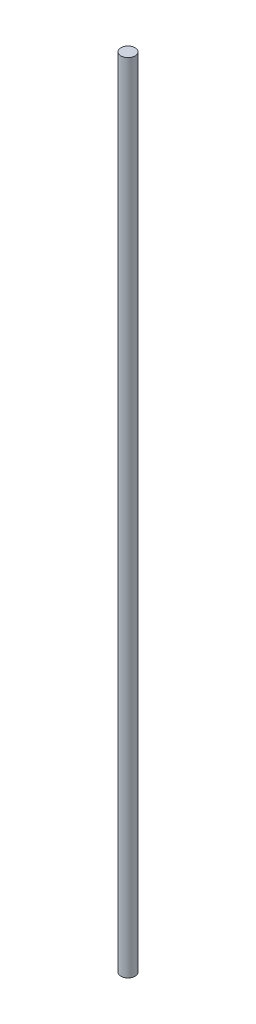
SolidWorks part; units mm, degrees
ref_plane "Front Plane" through (0, 0, 0) normal (0, 0, 1) x (1, 0, 0)
ref_plane "Top Plane" through (0, 0, 0) normal (0, 1, 0) x (1, 0, 0)
ref_plane "Right Plane" through (0, 0, 0) normal (1, 0, 0) x (0, 0, -1)
sketch "Sketch1" plane through (0, 0, 0) normal (0, 1, 0) x (1, 0, 0)
  circle A0 centre (0, 0) radius 2.5
  dimension "D1" = 5
extrude "Boss-Extrude1" add sketch "Sketch1" along normal blind 250 and the other way blind 31.0217
